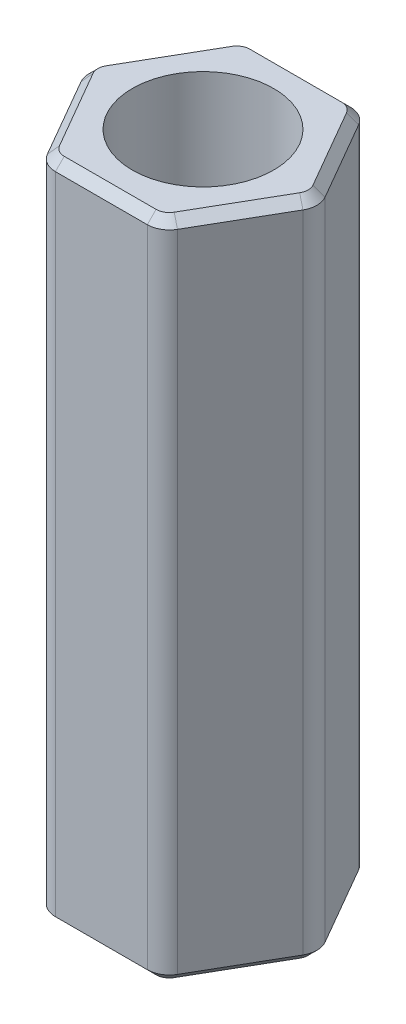
SolidWorks part; units mm, degrees
ref_plane "Front Plane" through (0, 0, 0) normal (0, 0, 1) x (1, 0, 0)
ref_plane "Top Plane" through (0, 0, 0) normal (0, 1, 0) x (1, 0, 0)
ref_plane "Right Plane" through (0, 0, 0) normal (1, 0, 0) x (0, 0, -1)
sketch "Sketch1" plane through (0, 0, 0) normal (0, 1, 0) x (1, 0, 0)
  line L1 (1.3279, -2.3) -> (2.6558, 0)
  line L2 (2.6558, 0) -> (1.3279, 2.3)
  line L3 (1.3279, 2.3) -> (-1.3279, 2.3)
  line L4 (-1.3279, 2.3) -> (-2.6558, 0)
  line L5 (-2.6558, 0) -> (-1.3279, -2.3)
  line L6 (-1.3279, -2.3) -> (1.3279, -2.3)
  circle A0 centre (0, 0) radius 2.3 construction
  dimension "D1" = 4.6
extrude "Boss-Extrude1" add sketch "Sketch1" along normal blind 15
sketch "Sketch2" plane through (0, 15, 0) normal (0, 1, 0) x (1, 0, 0)
  circle A0 centre (0, 0) radius 1.6
  dimension "D1" = 3.2
extrude "Cut-Extrude1" cut sketch "Sketch2" against normal through all
fillet "Fillet1" radius 0.5 6 edges at (-1.3279, 7.5, 2.3) (-2.6558, 7.5, 0) (-1.3279, 7.5, -2.3) (1.3279, 7.5, -2.3) (2.6558, 7.5, 0) (1.3279, 7.5, 2.3)
chamfer "Chamfer1" distance 0.2 angle 45 24 edges at (-1.2892, 0, 2.233) (-1.9919, 0, 1.15) (0, 0, 2.3) (-2.5785, 0, 0) (1.2892, 0, 2.233) (-1.9919, 0, -1.15) (1.9919, 0, 1.15) (-1.2892, 0, -2.233) (2.5785, 0, 0) (0, 0, -2.3) (1.9919, 0, -1.15) (1.2892, 0, -2.233) (0, 15, -2.3) (-1.9919, 15, 1.15) (-1.2892, 15, 2.233) (-2.5785, 15, 0) (0, 15, 2.3) (-1.9919, 15, -1.15) (1.2892, 15, 2.233) (-1.2892, 15, -2.233) (1.9919, 15, 1.15) (2.5785, 15, 0) (1.2892, 15, -2.233) (1.9919, 15, -1.15)
